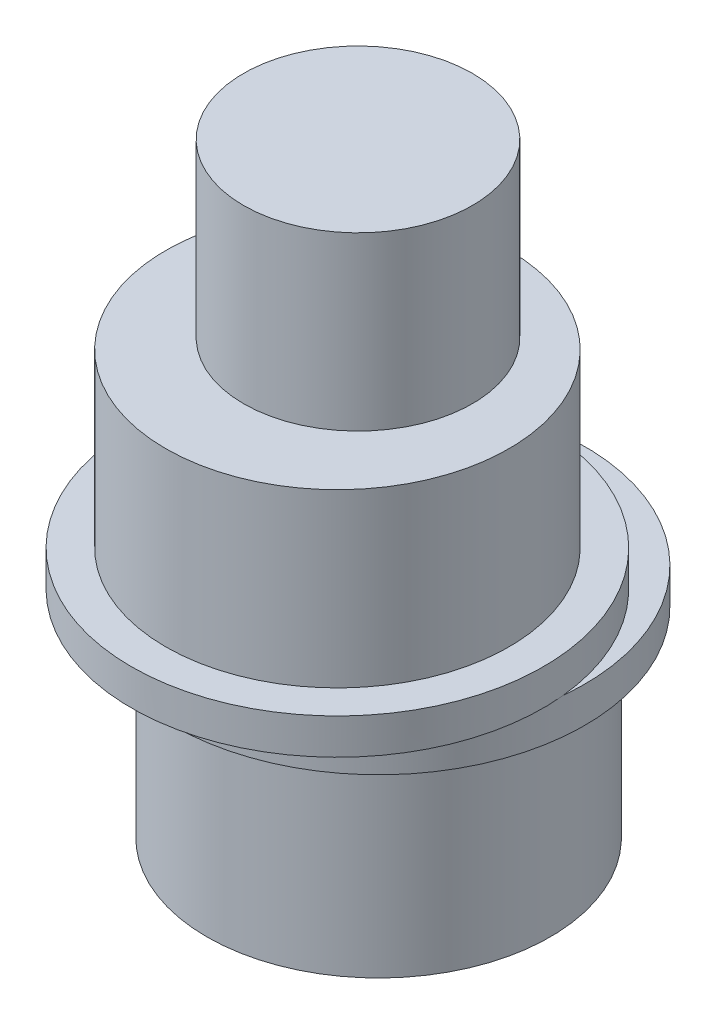
SolidWorks part; units mm, degrees
ref_plane "Front Plane" through (0, 0, 0) normal (0, 0, 1) x (1, 0, 0)
ref_plane "Top Plane" through (0, 0, 0) normal (0, 1, 0) x (1, 0, 0)
ref_plane "Right Plane" through (0, 0, 0) normal (1, 0, 0) x (0, 0, -1)
sketch "Sketch1" plane through (0, 0, 0) normal (0, 1, 0) x (1, 0, 0)
  circle A0 centre (0, 0.72) radius 6
  dimension "D1" = 12
  dimension "D2" = 0.72
extrude "Boss-Extrude1" add sketch "Sketch1" along normal blind 7
sketch "Sketch2" plane through (0, 7, 0) normal (0, 1, 0) x (1, 0, 0)
  circle A0 centre (0, 0.72) radius 7.2
  dimension "D1" = 14.4
extrude "Boss-Extrude2" add sketch "Sketch2" along normal blind 1.25
sketch "Sketch3" plane through (0, 8.25, 0) normal (0, 1, 0) x (1, 0, 0)
  circle A0 centre (0, -0.72) radius 7.2
  dimension "D1" = 14.4
  dimension "D2" = 0.72
extrude "Boss-Extrude3" add sketch "Sketch3" along normal blind 1.25
sketch "Sketch4" plane through (0, 9.5, 0) normal (0, 1, 0) x (1, 0, 0)
  circle A0 centre (0, -0.72) radius 6
  dimension "D1" = 12
  dimension "D2" = 0.72
extrude "Boss-Extrude4" add sketch "Sketch4" along normal blind 6
sketch "Sketch5" plane through (0, 0, 0) normal (0, -1, 0) x (1, 0, 0)
  line L0 (0, 0) -> (0, 2.1) construction
  line L1 (1.4902, 2.1) -> (-1.4902, 2.1)
  arc A0 (-1.4902, 2.1) -> (1.4902, 2.1) centre (0, 0) ccw
  point P7 (0, 2.1)
  dimension "D1" = 5.15
  dimension "D2" = 2.1
extrude "Cut-Extrude2" cut sketch "Sketch5" against normal blind 11 and the other way through all
sketch "Sketch6" plane through (0, 15.5, 0) normal (0, 1, 0) x (1, 0, 0)
  circle A0 centre (0, 0) radius 4
  dimension "D1" = 8
extrude "Boss-Extrude5" add sketch "Sketch6" along normal blind 6
sketch "Sketch7" plane through (0, 15.5, 0) normal (0, 1, 0) x (1, 0, 0)
  line L0 (0, 5.28) -> (0, -6.72) construction
  circle A0 centre (0, -0.72) radius 6 construction
  circle A1 centre (0, -0.72) radius 6 construction
